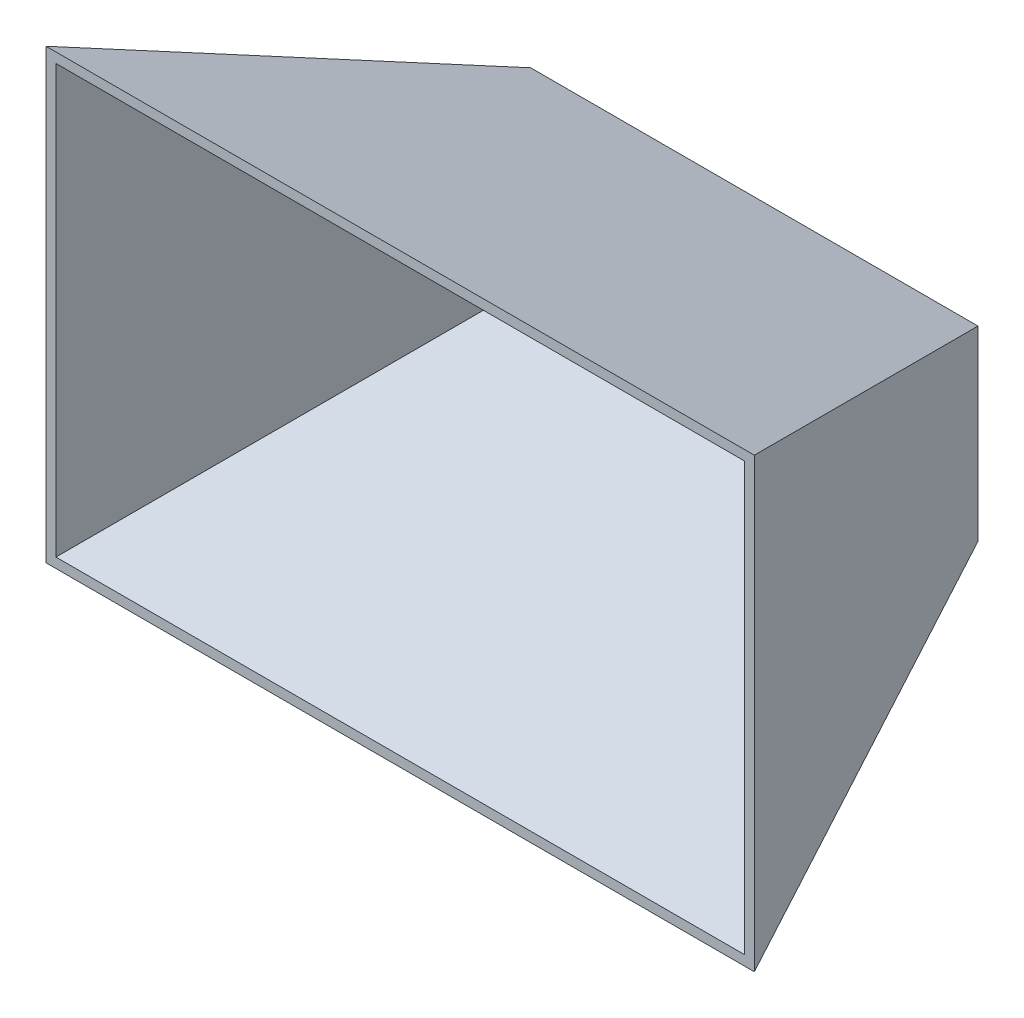
SolidWorks part; units mm, degrees
ref_plane "Front Plane" through (0, 0, 0) normal (0, 0, 1) x (1, 0, 0)
ref_plane "Top Plane" through (0, 0, 0) normal (0, 1, 0) x (1, 0, 0)
ref_plane "Right Plane" through (0, 0, 0) normal (1, 0, 0) x (0, 0, -1)
sketch "Sketch17" plane through (0, 0, 0) normal (0, 0, 1) x (1, 0, 0)
  line L1 (-87.3194, -550.7651) -> (392.6806, -550.7651)
  line L2 (-87.3194, -550.7651) -> (-87.3194, -350.7651)
  line L3 (-87.3194, -350.7651) -> (392.6806, -350.7651)
  line L4 (392.6806, -550.7651) -> (392.6806, -350.7651)
  dimension "D1" = 480
  dimension "D2" = 200
ref_plane "Plane1" through (0, 0, 380) normal (0, 0, 1) x (1, 0, 0)
sketch "Sketch18" plane through (0, 0, 380) normal (0, 0, 1) x (1, 0, 0)
  line L8 (-227.3194, -690.7651) -> (532.6806, -690.7651)
  line L9 (532.6806, -690.7651) -> (532.6806, -210.7651)
  line L10 (532.6806, -210.7651) -> (-227.3194, -210.7651)
  line L11 (-227.3194, -210.7651) -> (-227.3194, -690.7651)
  line L12 (-227.3194, -690.7651) -> (532.6806, -690.7651)
  line L13 (532.6806, -690.7651) -> (532.6806, -210.7651)
  line L14 (532.6806, -210.7651) -> (-227.3194, -210.7651)
  line L15 (-227.3194, -210.7651) -> (-227.3194, -690.7651)
  dimension "D1" = 140
loft "Loft1" add profiles "Sketch17", "Sketch18"
shell "Shell1" thickness 10
sketch "Sketch19" plane through (0, 0, 10) normal (0, 0, 1) x (1, 0, 0)
  line L1 (-80.3465, -357.738) -> (105.7077, -357.738)
  line L2 (-80.3465, -357.738) -> (-80.3465, -543.7922)
  line L3 (-80.3465, -543.7922) -> (385.7077, -543.7922)
  line L5 (385.7077, -543.7922) -> (385.7077, -357.738)
  line L6 (385.7077, -357.738) -> (105.7077, -357.738)
extrude "Cut-Extrude14" cut sketch "Sketch19" against normal through all contours L6 L1 L2 L3 L5
